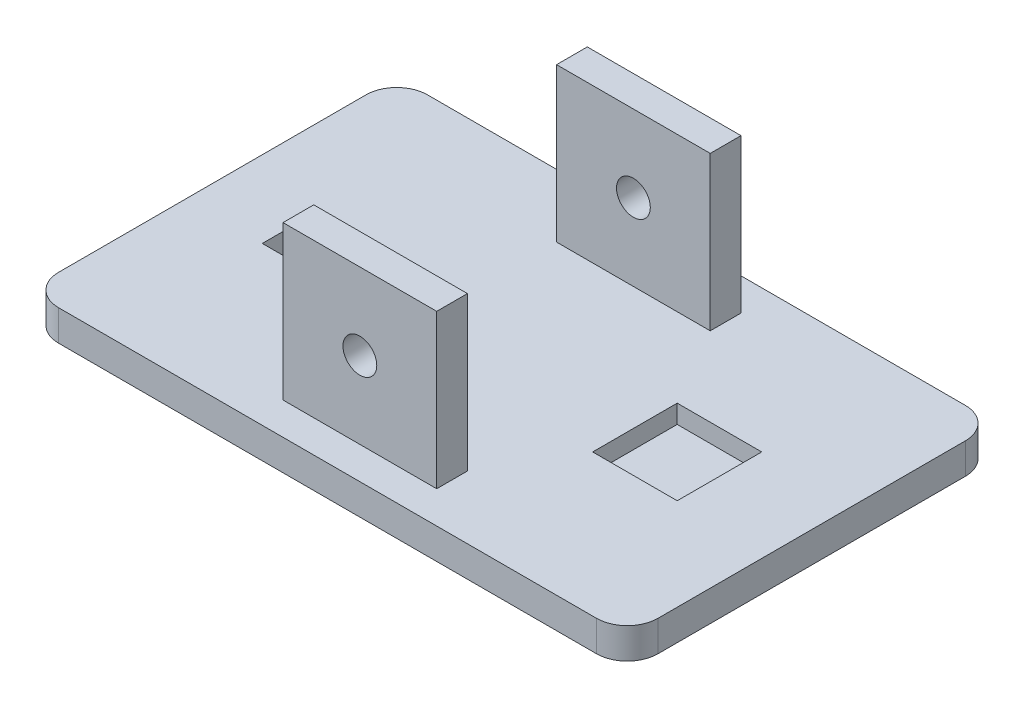
SolidWorks part; units mm, degrees
ref_plane "Ön Düzlem" through (0, 0, 0) normal (0, 0, 1) x (1, 0, 0)
ref_plane "Üst Düzlem" through (0, 0, 0) normal (0, 1, 0) x (1, 0, 0)
ref_plane "Sağ Düzlem" through (0, 0, 0) normal (1, 0, 0) x (0, 0, -1)
sketch "Çizim1" plane through (0, 0, 0) normal (0, 1, 0) x (1, 0, 0)
  line L1 (-12.7384, 8.6163) -> (22.2616, 8.6163)
  line L2 (-14.7384, 6.6163) -> (-14.7384, -13.3837)
  line L3 (-12.7384, -15.3837) -> (22.2616, -15.3837)
  line L4 (24.2616, 6.6163) -> (24.2616, -13.3837)
  arc A0 (-14.7384, -13.3837) -> (-12.7384, -15.3837) centre (-12.7384, -13.3837) ccw
  arc A1 (22.2616, -15.3837) -> (24.2616, -13.3837) centre (22.2616, -13.3837) ccw
  arc A2 (24.2616, 6.6163) -> (22.2616, 8.6163) centre (22.2616, 6.6163) ccw
  arc A3 (-12.7384, 8.6163) -> (-14.7384, 6.6163) centre (-12.7384, 6.6163) ccw
  point P6 (-14.7384, -15.3837)
  point P11 (24.2616, 8.6163)
  point P14 (-14.7384, 8.6163)
  dimension "D3" = 2
  dimension "D1" = 39
  dimension "D2" = 24
extrude "Yükseklik-Ekstrüzyon1" add sketch "Çizim1" along normal blind 2
sketch "Çizim2" plane through (0, 2, 0) normal (0, 1, 0) x (1, 0, 0)
  line L0 (-12.7384, -15.3837) -> (22.2616, -15.3837) construction
  line L1 (-0.2384, -11.2837) -> (9.7616, -11.2837)
  line L2 (-0.2384, -11.2837) -> (-0.2384, -13.2837)
  line L3 (-0.2384, -13.2837) -> (9.7616, -13.2837)
  line L4 (9.7616, -11.2837) -> (9.7616, -13.2837)
  line L5 (-14.7384, 6.6163) -> (-14.7384, -13.3837) construction
  line L8 (-0.2384, 4.5163) -> (-0.2384, 6.5163)
  line L9 (9.7616, 4.5163) -> (9.7616, 6.5163)
  line L10 (-0.2384, 4.5163) -> (9.7616, 4.5163)
  line L11 (-0.2384, 6.5163) -> (9.7616, 6.5163)
  dimension "D1" = 10
  dimension "D2" = 2
  dimension "D3" = 2.1
  dimension "D4" = 14.5
extrude "Yükseklik-Ekstrüzyon2" add sketch "Çizim2" along normal blind 10
sketch "Çizim3" plane through (0, 0, 13.2837) normal (0, 0, 1) x (1, 0, 0)
  line L0 (-0.2384, 2) -> (9.7616, 2) construction
  circle A0 centre (4.7616, 7) radius 1.1
  dimension "D1" = 5
extrude "Kes-Ekstrüzyon1" cut sketch "Çizim3" against normal blind 30
sketch "Çizim4" plane through (0, 2, 0) normal (0, 1, 0) x (1, 0, 0)
  line L0 (22.2616, 8.6163) -> (-12.7384, 8.6163) construction
  line L1 (-9.7384, -1.6337) -> (-1.7384, -1.6337)
  line L2 (-9.7384, -1.6337) -> (-9.7384, -5.1337)
  line L3 (-9.7384, -5.1337) -> (-1.7384, -5.1337)
  line L4 (-1.7384, -1.6337) -> (-1.7384, -5.1337)
  line L5 (-14.7384, 6.6163) -> (-14.7384, -13.3837) construction
  dimension "D1" = 8
  dimension "D2" = 3.5
  dimension "D3" = 10.25
  dimension "D4" = 5
extrude "Kes-Ekstrüzyon2" cut sketch "Çizim4" against normal blind 30
sketch "Çizim5" plane through (0, 2, 0) normal (0, 1, 0) x (1, 0, 0)
  line L0 (22.2616, 8.6163) -> (-12.7384, 8.6163) construction
  line L1 (12.7616, -0.6337) -> (18.2616, -0.6337)
  line L2 (12.7616, -0.6337) -> (12.7616, -6.1337)
  line L3 (12.7616, -6.1337) -> (18.2616, -6.1337)
  line L4 (18.2616, -0.6337) -> (18.2616, -6.1337)
  line L5 (24.2616, -13.3837) -> (24.2616, 6.6163) construction
  dimension "D1" = 5.5
  dimension "D2" = 5.5
  dimension "D3" = 9.25
  dimension "D4" = 6
extrude "Kes-Ekstrüzyon3" cut sketch "Çizim5" against normal blind 1.2
